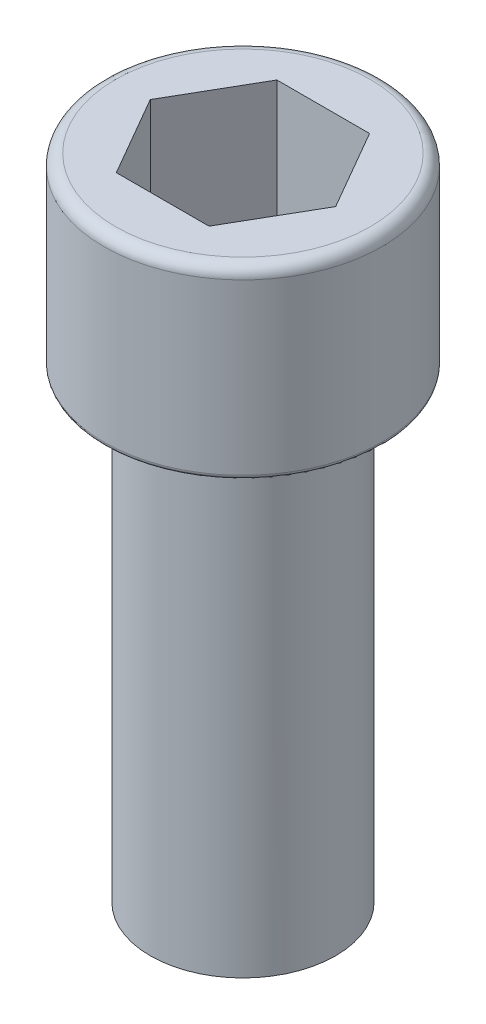
SolidWorks part; units mm, degrees
ref_plane "Front Plane" through (0, 0, 0) normal (0, 0, 1) x (1, 0, 0)
ref_plane "Top Plane" through (0, 0, 0) normal (0, 1, 0) x (1, 0, 0)
ref_plane "Right Plane" through (0, 0, 0) normal (1, 0, 0) x (0, 0, -1)
sketch "Sketch1" plane through (0, 0, 0) normal (0, 1, 0) x (1, 0, 0)
  circle A1 centre (0, 0) radius 3
  dimension "D1" = 6
extrude "Boss-Extrude1" add sketch "Sketch1" along normal blind 4
fillet "Fillet1" radius 0.25 1 edges at (0, 4, 3)
sketch "Sketch2" plane through (0, 4, 0) normal (0, 1, 0) x (1, 0, 0)
  line L0 (-2.75, 0) -> (2.75, 0) construction
  line L1 (2, 0) -> (1, 1.7321)
  line L2 (1, 1.7321) -> (-1, 1.7321)
  line L3 (-1, 1.7321) -> (-2, 0)
  line L4 (-2, 0) -> (-1, -1.7321)
  line L5 (-1, -1.7321) -> (1, -1.7321)
  line L6 (1, -1.7321) -> (2, 0)
  circle A0 centre (0, 0) radius 1.7321 construction
  circle A2 centre (0, 0) radius 2.75 construction
  point P14 (0, 0)
  dimension "D1" = 0.75
extrude "Cut-Extrude1" cut sketch "Sketch2" against normal blind 3
fillet "Fillet2" radius 0.1 1 edges at (0, 0, 3)
sketch "Sketch3" plane through (0, 0, 0) normal (0, -1, 0) x (1, 0, 0)
  circle A0 centre (0, 0) radius 2
  dimension "D1" = 4
extrude "Boss-Extrude2" add sketch "Sketch3" along normal blind 10
